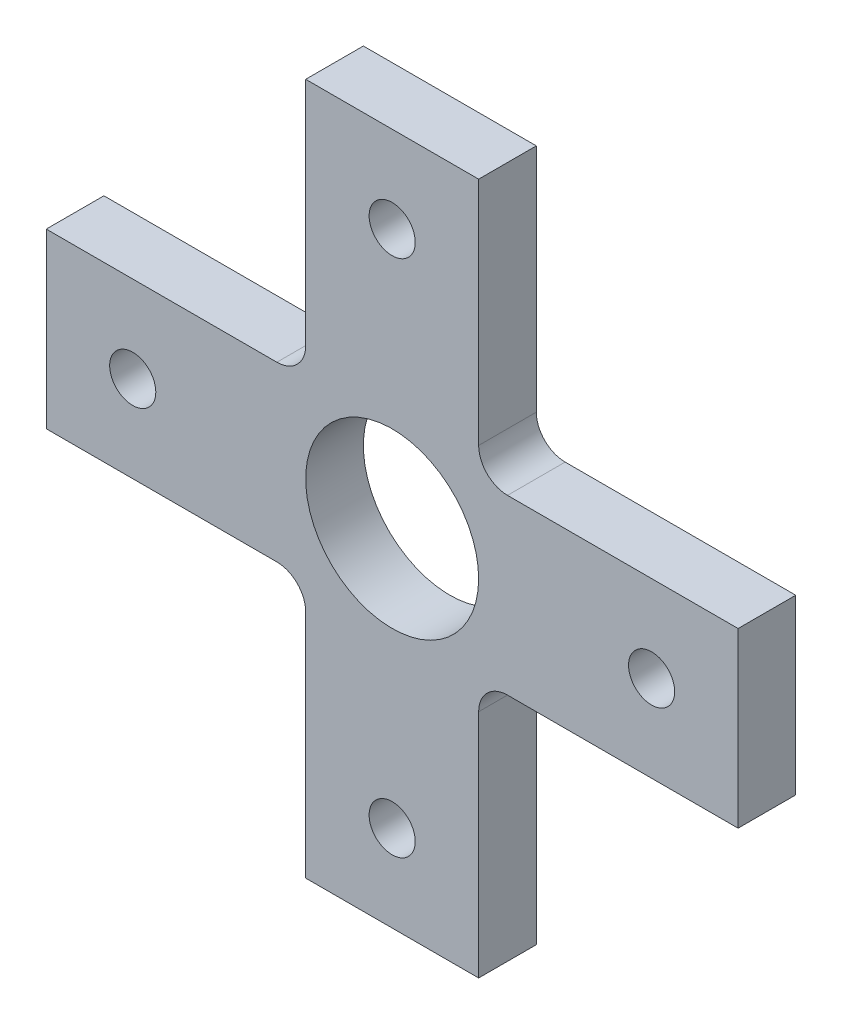
SolidWorks part; units mm, degrees
ref_plane "前视基准面" through (0, 0, 0) normal (0, 0, 1) x (1, 0, 0)
ref_plane "上视基准面" through (0, 0, 0) normal (0, 1, 0) x (1, 0, 0)
ref_plane "右视基准面" through (0, 0, 0) normal (1, 0, 0) x (0, 0, -1)
ref_plane "基准面1" through (0, 0, -5) normal (0, 0, 1) x (1, 0, 0)
sketch "草图6" plane through (0, 0, -5) normal (0, 0, 1) x (1, 0, 0)
  line L0 (-15, 60) -> (15, 60)
  line L1 (15, 60) -> (15, 20)
  line L2 (20, 15) -> (60, 15)
  line L3 (60, 15) -> (60, -15)
  line L4 (60, -15) -> (20, -15)
  line L5 (15, -20) -> (15, -60)
  line L6 (15, -60) -> (-15, -60)
  line L7 (-15, -60) -> (-15, -20)
  line L8 (-20, -15) -> (-60, -15)
  line L9 (-60, -15) -> (-60, 15)
  line L10 (-60, 15) -> (-20, 15)
  line L11 (-15, 20) -> (-15, 60)
  arc A0 (15, 20) -> (20, 15) centre (20, 20) ccw
  arc A1 (20, -15) -> (15, -20) centre (20, -20) ccw
  arc A2 (-15, -20) -> (-20, -15) centre (-20, -20) ccw
  arc A3 (-20, 15) -> (-15, 20) centre (-20, 20) ccw
extrude "凸台-拉伸6" add sketch "草图6" along normal blind 10
sketch "草图7" plane through (0, 0, -5) normal (0, 0, 1) x (1, 0, 0)
  circle A0 centre (0, 0) radius 15
extrude "切除-拉伸1" cut sketch "草图7" against normal mid plane 242
sketch "草图8" plane through (0, 0, -5) normal (0, 0, 1) x (1, 0, 0)
  circle A0 centre (45, 0) radius 4
  circle A1 centre (-45, 0) radius 4
  circle A2 centre (0, 45) radius 4
  circle A3 centre (0, -45) radius 4
extrude "切除-拉伸2" cut sketch "草图8" against normal mid plane 242
